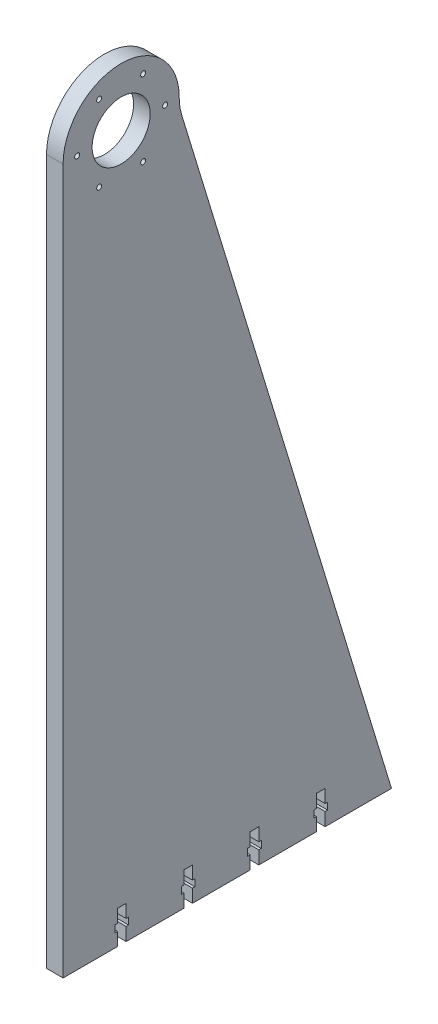
SolidWorks part; units mm, degrees
ref_plane "Спереди" through (0, 0, 0) normal (0, 0, 1) x (1, 0, 0)
ref_plane "Сверху" through (0, 0, 0) normal (0, 1, 0) x (1, 0, 0)
ref_plane "Справа" through (0, 0, 0) normal (1, 0, 0) x (0, 0, -1)
sketch "Эскиз2" plane through (0, 0, 0) normal (1, 0, 0) x (0, 0, -1)
  line L0 (0, 425) -> (0, 0)
  line L2 (71.5218, 414.7918) -> (198, 0)
  line L3 (198, 0) -> (0, 0)
  line L7 (0, 425) -> (70, 425) construction
  arc A0 (0, 425) -> (70, 425) centre (35, 425) cw
  arc A1 (70, 425) -> (71.5218, 414.7918) centre (105, 425) ccw
  circle A4 centre (35, 425) radius 17.5
  dimension "D2" = 35
  dimension "D3" = 35
  dimension "D5" = 35
  dimension "D1" = 198
  dimension "D4" = 425
extrude "Бобышка-Вытянуть1" add sketch "Эскиз2" along normal blind 10
sketch "Эскиз3" plane through (0, 0, 0) normal (-1, 0, 0) x (0, 0, 1)
  line L0 (-158, 0) -> (-158, 7.9)
  line L1 (0, 0) -> (-198, 0) construction
  line L2 (-158, 7.9) -> (-159.5, 7.9)
  line L3 (-159.5, 7.9) -> (-159.5, 12.1)
  line L4 (-159.5, 12.1) -> (-158, 12.1)
  line L5 (-158, 12.1) -> (-158, 20)
  line L6 (-158, 20) -> (-152.8, 20)
  line L7 (-152.8, 20) -> (-152.8, 12.1)
  line L8 (-152.8, 12.1) -> (-151.3, 12.1)
  line L9 (-151.3, 12.1) -> (-151.3, 7.9)
  line L10 (-151.3, 7.9) -> (-152.8, 7.9)
  line L11 (-152.8, 7.9) -> (-152.8, 0)
  line L12 (-158, 12.1) -> (-152.8, 12.1) construction
  line L13 (-158, 7.9) -> (-152.8, 7.9) construction
  line L14 (-158, 0) -> (-152.8, 0)
  point P10 (-151.3, 10)
  dimension "D1" = 8.2
  dimension "D2" = 5.2
  dimension "D3" = 5.2
  dimension "D4" = 4.2
  dimension "D5" = 20
  dimension "D6" = 40
extrude "Вырез-Вытянуть2" cut sketch "Эскиз3" against normal blind 10
pattern_linear "Линейный массив1" count 4 spacing 40 along (0, 0, 1) of "Вырез-Вытянуть2"
sketch "Эскиз4" [suppressed] plane through (0, 0, 0) normal (0, 1, 0) x (1, 0, 0)
  line L0 (-111, 99) -> (0, 99) construction
  line L1 (0, 78) -> (0, 112.8) construction
  circle A0 centre (-111, 99) radius 156
  circle A1 centre (-111, 99) radius 146
  circle A2 centre (-111, 99) radius 175
  circle A3 centre (-111, 99) radius 165.5 construction
  circle A4 centre (-111, 99) radius 200
  circle A5 centre (-111, 99) radius 37.02
  dimension "D2" = 10
  dimension "D3" = 350
  dimension "D1" = 312
  dimension "D5" = 9.5
  dimension "D6" = 400
  dimension "D4" = 111
sketch "Эскиз5" plane through (0, 0, 0) normal (0, -1, 0) x (1, 0, 0)
  line L0 (5, 0) -> (5, -198) construction
  line L1 (10, 0) -> (0, 0) construction
  line L2 (10, -198) -> (0, -198) construction
  line L3 (10, -32.8) -> (0, -32.8) construction
  line L4 (10, -72.8) -> (0, -72.8) construction
  line L5 (10, -112.8) -> (0, -112.8) construction
  line L6 (10, -152.8) -> (0, -152.8) construction
  circle A0 centre (5, -35.4) radius 2.6
  circle A1 centre (5, -75.4) radius 2.6
  circle A2 centre (5, -115.4) radius 2.6
  circle A3 centre (5, -155.4) radius 2.6
  dimension "D1" = 5.2
  dimension "D2" = 5.2
  dimension "D3" = 5.2
  dimension "D4" = 5.2
sketch "Эскиз6" plane through (10, 0, 0) normal (1, 0, 0) x (0, 0, -1)
  circle A0 centre (35, 425) radius 26.5 construction
  arc A2 (70, 425) -> (0, 425) centre (35, 425) ccw construction
  circle A3 centre (8.5, 425) radius 1.5
  dimension "D1" = 8.5
  dimension "D2" = 3
extrude "Вырез-Вытянуть3" cut sketch "Эскиз6" against normal blind 10
pattern_circular "Круговой массив1" count 6 over 360 about axis through (0, 425, -35) along (1, 0, 0) of "Вырез-Вытянуть3"
